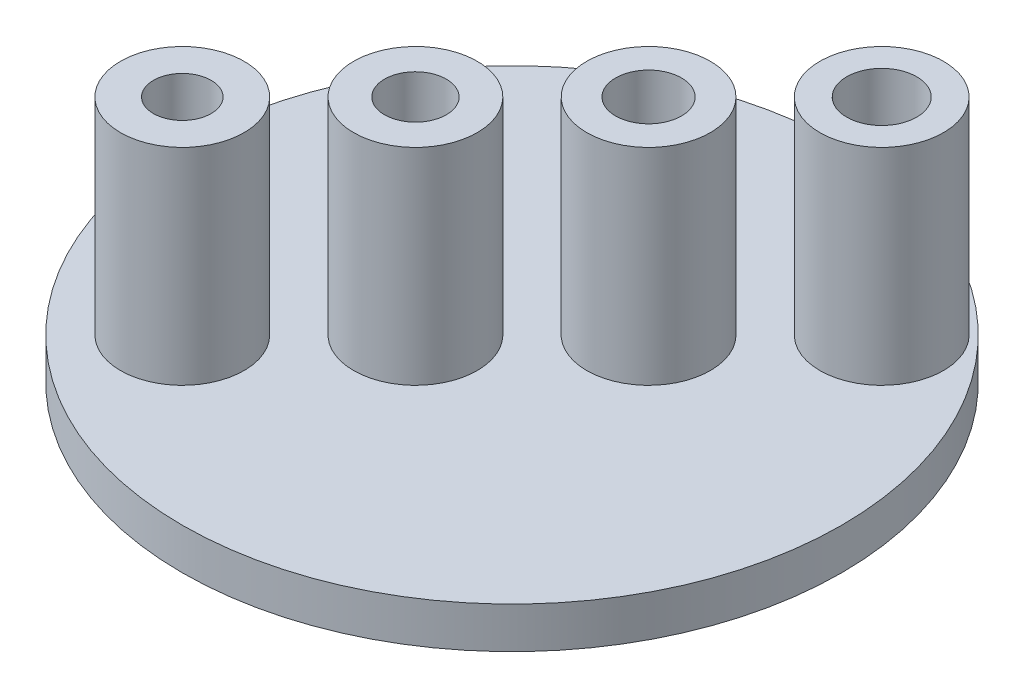
SolidWorks part; units mm, degrees
ref_plane "Front Plane" through (0, 0, 0) normal (0, 0, 1) x (1, 0, 0)
ref_plane "Top Plane" through (0, 0, 0) normal (0, 1, 0) x (1, 0, 0)
ref_plane "Right Plane" through (0, 0, 0) normal (1, 0, 0) x (0, 0, -1)
sketch "Sketch3" plane through (0, 0, 0) normal (0, 1, 0) x (1, 0, 0)
  circle A0 centre (0, 0) radius 10.16
  dimension "D1" = 20.32
extrude "Boss-Extrude1" add sketch "Sketch3" along normal blind 1.27
sketch "Sketch4" plane through (0, 1.27, 0) normal (0, 1, 0) x (1, 0, 0)
  circle A0 centre (-5.08, -5.08) radius 1.905
  point P2 (0, 0)
  point P5 (-0.85, 4.2895)
  dimension "D1" = 3.81
  dimension "D2" = 5.08
  dimension "D3" = 5.08
extrude "Boss-Extrude2" add sketch "Sketch4" along normal blind 6.35
sketch "Sketch5" plane through (0, 1.27, 0) normal (0, 1, 0) x (1, 0, 0)
  line L0 (0, 0) -> (-5.08, -5.08)
  point P4 (0, 0)
pattern_linear "LPattern1" count 4 spacing 5.08 along (0.7071, 0, -0.7071) of "Boss-Extrude2"
sketch "Sketch6" plane through (0, 7.62, 0) normal (0, 1, 0) x (1, 0, 0)
  circle A0 centre (-5.08, -5.08) radius 0.889
  dimension "D1" = 1.778
extrude "Cut-Extrude1" cut sketch "Sketch6" against normal up to surface (6.35 mm away) up to face at (5.6963, 1.27, -3.7913)
sketch "Sketch7" plane through (0, 7.62, 0) normal (0, 1, 0) x (1, 0, 0)
  circle A0 centre (-1.4879, -1.4879) radius 0.9525
  dimension "D1" = 1.905
extrude "Cut-Extrude2" cut sketch "Sketch7" against normal up to surface (6.35 mm away) up to face at (5.6963, 1.27, -3.7913)
sketch "Sketch8" plane through (0, 7.62, 0) normal (0, 1, 0) x (1, 0, 0)
  circle A0 centre (2.1042, 2.1042) radius 1.016
  dimension "D1" = 2.032
extrude "Cut-Extrude3" cut sketch "Sketch8" against normal up to surface (6.35 mm away) up to face at (5.6963, 1.27, -3.7913)
sketch "Sketch9" plane through (0, 7.62, 0) normal (0, 1, 0) x (1, 0, 0)
  circle A0 centre (5.6963, 5.6963) radius 1.0795
  dimension "D1" = 2.159
extrude "Cut-Extrude4" cut sketch "Sketch9" against normal up to surface (6.35 mm away) up to face at (5.6963, 1.27, -3.7913)
